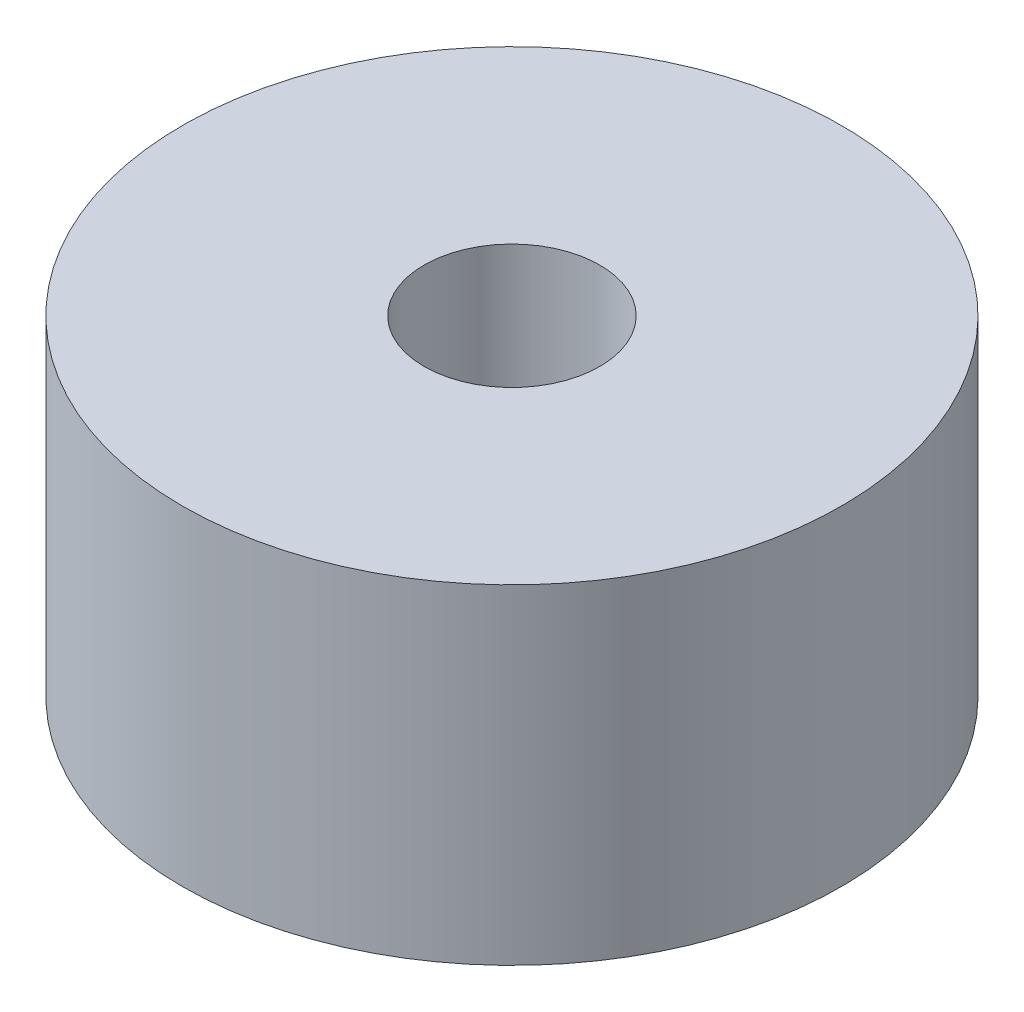
SolidWorks part; units mm, degrees
ref_plane "Front Plane" through (0, 0, 0) normal (0, 0, 1) x (1, 0, 0)
ref_plane "Top Plane" through (0, 0, 0) normal (0, 1, 0) x (1, 0, 0)
ref_plane "Right Plane" through (0, 0, 0) normal (1, 0, 0) x (0, 0, -1)
sketch "Sketch2" plane through (0, 0, 0) normal (0, 1, 0) x (1, 0, 0)
  circle A0 centre (0, 0) radius 15
  point P0 (0, 0)
  dimension "D1" = 30
extrude "Boss-Extrude1" add sketch "Sketch2" along normal blind 15
sketch "Sketch3" plane through (0, 15, 0) normal (0, 1, 0) x (1, 0, 0)
  circle A0 centre (0, 0) radius 4
extrude "Cut-Extrude1" cut sketch "Sketch3" against normal blind 10
